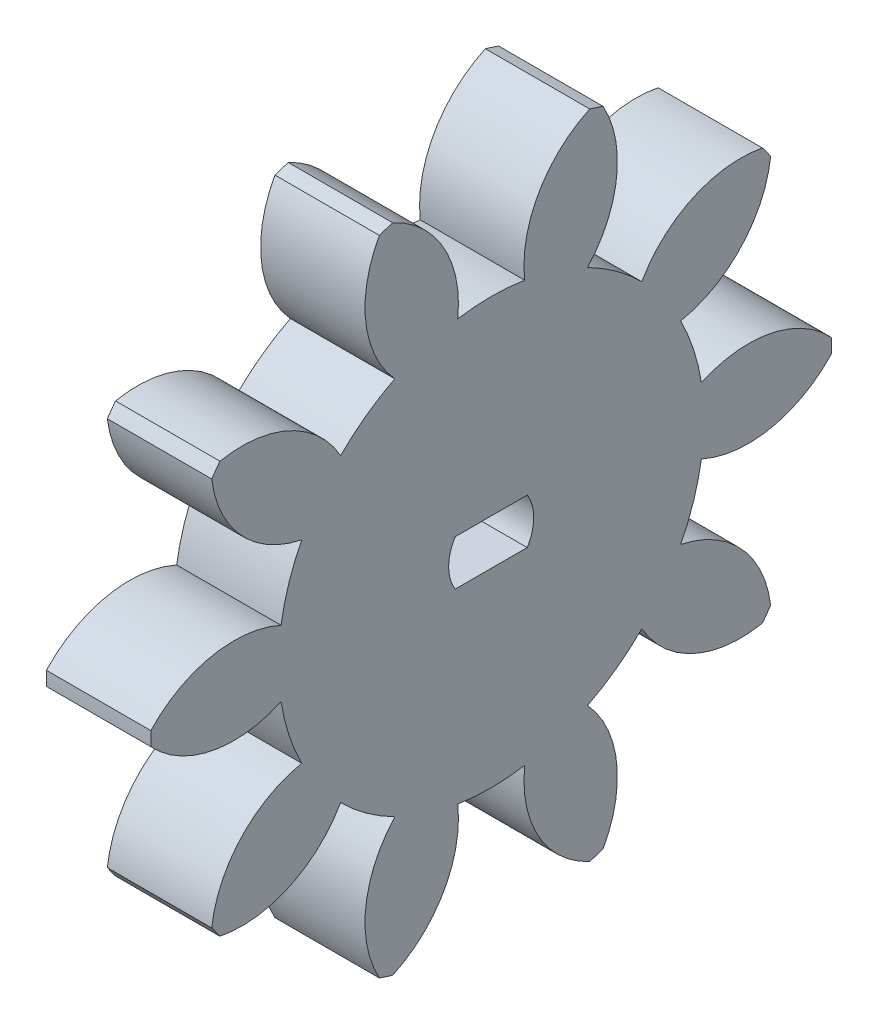
SolidWorks part; units mm, degrees
ref_plane "Plane1" through (0, 0, 0) normal (0, 0, 1) x (1, 0, 0)
ref_plane "Plane2" through (0, 0, 0) normal (0, 1, 0) x (1, 0, 0)
ref_plane "Plane3" through (0, 0, 0) normal (1, 0, 0) x (0, 0, -1)
sketch "HoldingSke" plane through (0, 0, 0) normal (0, 1, 0) x (1, 0, 0)
  line L0 (0, 0) -> (200.1129, -35.2853)
  line L1 (-15, 0) -> (100, 0) construction
  line L2 (0, 0) -> (-2.1039, 2.3779)
  line L3 (0, 0) -> (-11.863, 4.5341)
  line L4 (0, 0) -> (8.5048, 1.4996)
  line L5 (0, 0) -> (-47.5972, -17.7524)
  line L6 (0, 0) -> (-4.8428, -3.2675)
  line L7 (-2.1039, 2.3779) -> (8.8308, 51.9871)
  line L8 (-76.2, 54.61) -> (-71.1708, 54.61)
  line L9 (-71.009, 38.7566) -> (-53.1078, 45.2721)
  line L10 (-76.2, 71.12) -> (104.1128, 71.12)
  line L11 (0, 0) -> (-5.842, 0)
  line L12 (-76.2, 101.6) -> (-76.0857, 101.6)
  line L13 (24.9733, 27.94) -> (52.9518, 28.4284)
  line L14 (24.9733, 27.94) -> (24.9746, 27.94)
  line L15 (24.9733, 27.94) -> (100.4006, 29.5858)
  circle A0 centre (0, 0) radius 2.3812
  circle A1 centre (0, 0) radius 11.905
  circle A2 centre (0, 0) radius 38.1
  circle A3 centre (0, 0) radius 2.3812
  dimension "MHD" = 23.81
  dimension "Hub_dia" = 76.2
  dimension "Bore" = 4.7625
  dimension "MBD" = 4.7625
  dimension "Num_teeth" = 10
  dimension "Pitch" = 203.2
  dimension "Overall_len" = 50.8
  dimension "Show_teeth" = 10
  dimension "Thickness" = 5.842
  dimension "OAL" = 50.8001
  dimension "T_dim" = 5.0292
  dimension "Ap" = 20
  dimension "H" = 19.05
  dimension "Pitch_radius" = 180.3128
  dimension "Width" = 5.842
  dimension "Backlash" = 0.1143
  dimension "Addendum_fac" = 1
  dimension "Dedendum_fac" = 1.25
  dimension "Clearance_fac" = 0.25
  dimension "Dedendum_add" = 0.0013
sketch "BasProSke" plane through (0, 0, 0) normal (0, 1, 0) x (1, 0, 0)
  line L0 (-10, 0) -> (60, 0) construction
  line L1 (0, 0) -> (0, 19.05)
  line L2 (0, 0) -> (5.842, 0)
  line L3 (5.842, 0) -> (5.842, 19.05)
  line L4 (5.842, 19.05) -> (0, 19.05)
  dimension "Thickness" = 5.842
  dimension "Diameter" = 38.1
revolve "Base-Revolve" add sketch "BasProSke" angle 360 about L0
sketch "TooCutSke" plane through (0, 0, 0) normal (1, 0, 0) x (0, 0, -1)
  line L1 (0, 0) -> (0, 107) construction
  line L2 (0, 0) -> (-2.683, 15.6466) construction
  line L3 (0, 0) -> (-9.7093, 29.8821) construction
  line L4 (-2.683, 15.6466) -> (-4.8546, 14.941) construction
  arc A0 (1.8735, 11.7566) -> (-1.8735, 11.7566) centre (0, 0) ccw
  arc A1 (5.5485, 18.2506) -> (-5.5485, 18.2506) centre (0, 0) ccw
  circle A2 centre (0, 0) radius 15.875 construction
  circle A3 centre (0, 0) radius 14.9176 construction
  arc A4 (-1.8735, 11.7566) -> (-5.5485, 18.2506) centre (-8.183, 12.4729) ccw
  arc A5 (5.5485, 18.2506) -> (1.8735, 11.7566) centre (8.183, 12.4729) ccw
  dimension "Root_dia" = 23.81
  dimension "Overcut_dia" = 38.1508
  dimension "Pitch_dia" = 31.75
  dimension "Base_dia" = 29.8352
  dimension "Flank_rad" = 6.35
  dimension "Half_ang" = 18
  dimension "Half_CT" = 2.2834
extrude "ToothCut" cut sketch "TooCutSke" along normal through all
fillet "Breaks" [suppressed] radius 0.0635
fillet "RootFillets" [suppressed] radius 0.795
pattern_circular "TeethCuts" count 10 every 36 about axis through (-10, 0, 0) along (1, 0, 0) of "ToothCut", "RootFillets", "Breaks"
sketch "HubNeaOneSke" plane through (0, 0, 0) normal (-1, 0, 0) x (0, 0, 1)
  circle A0 centre (0, 0) radius 11.905
  dimension "Diameter" = 23.81
extrude "HubNearOne" [suppressed] add sketch "HubNeaOneSke" along normal blind 44.9581
sketch "HubNeaBotSke" plane through (0, 0, 0) normal (-1, 0, 0) x (0, 0, 1)
  circle A0 centre (0, 0) radius 11.905
  dimension "Diameter" = 23.81
extrude "HubNearBoth" [suppressed] add sketch "HubNeaBotSke" along normal blind 22.479
ref_plane "FarPln" through (5.842, 0, 0) normal (1, 0, 0) x (0, 0, -1)
sketch "HubFarSke" plane through (5.842, 0, 0) normal (1, 0, 0) x (0, 0, -1)
  circle A0 centre (0, 0) radius 11.905
  dimension "Diameter" = 23.81
extrude "HubFar" [suppressed] add sketch "HubFarSke" along normal blind 22.479
sketch "BorSke" plane through (0, 0, 0) normal (1, 0, 0) x (0, 0, -1)
  circle A0 centre (0, 0) radius 2.3812
  dimension "Diameter" = 4.7625
extrude "Bore" cut sketch "BorSke" along normal mid plane 101.6001
sketch "KeySke" plane through (0, 0, 0) normal (1, 0, 0) x (0, 0, -1)
  line L0 (-0.127, 0) -> (-0.127, 2.6479)
  line L1 (-0.127, 2.6479) -> (0.127, 2.6479)
  line L2 (0.127, 2.6479) -> (0.127, 0)
  line L3 (0, 0) -> (0, 34) construction
  line L4 (-0.127, 0) -> (0.127, 0)
  dimension "Offset" = 2.648
  dimension "Width" = 0.254
extrude "Keyway" [suppressed] cut sketch "KeySke" along normal mid plane 101.6001
pattern_circular "Keyway2" [suppressed] count 2 every 90 about axis through (-10, 0, 0) along (1, 0, 0)
sketch "Sketch1" plane through (5.842, 0, 0) normal (1, 0, 0) x (0, 0, -1)
  line L0 (-4.4067, 4.572) -> (4.4067, 4.572)
  arc A0 (4.4067, 4.572) -> (-4.4067, 4.572) centre (0, 0) ccw
  point P5 (0, -6.35)
  dimension "D1" = 10.922
extrude "Boss-Extrude1" add sketch "Sketch1" against normal up to surface (5.842 mm away) up to face at (0, 0, -2.3812)
sketch "Sketch2" plane through (5.842, 0, 0) normal (1, 0, 0) x (0, 0, -1)
  line L0 (-2.177, 1.27) -> (2.177, 1.27)
  line L1 (-2.177, -1.27) -> (2.177, -1.27)
  line L2 (0, 1.27) -> (0, -1.27) construction
  arc A0 (-2.177, -1.27) -> (2.177, -1.27) centre (0, 0) ccw
  arc A1 (2.177, 1.27) -> (-2.177, 1.27) centre (0, 0) ccw
  point P9 (0, 0)
  point P10 (0, 0)
  dimension "D1" = 2.54
extrude "Boss-Extrude2" add sketch "Sketch2" against normal up to surface (5.842 mm away) up to face at (0, 0, -2.3812)
equation "' \"Pitch@HoldingSke\" = 4"
equation "' \"Num_teeth@HoldingSke\" = 12"
equation "' \"Ap@HoldingSke\" =  20"
equation "' \"Ap@HoldingSke\" = 20"
equation "' \"Width@HoldingSke\" = 0.5"
equation "' \"Hub_dia@HoldingSke\"= 1"
equation "' \"Hub_dia@HoldingSke\" = 1"
equation "' \"Overall_len@HoldingSke\" = 1.0"
equation "' \"Bore@HoldingSke\" = 0.75"
equation "' \"T_dim@HoldingSke\" = 0.85"
equation "' \"Width@KeySke\" = 0.25"
equation "' \"Show_teeth@HoldingSke\" = 13"
equation "' \"Backlash@HoldingSke\" = 0.009"
equation "' \"Addendum_fac@HoldingSke\" = 1.0"
equation "' \"Dedendum_fac@HoldingSke\" = 1.25"
equation "' \"Dedendum_add@HoldingSke\" = 0.00005"
equation "' \"Clearance_fac@HoldingSke\" = 0.25"
equation "' \"Pitch@HoldingSke\" = 0.5"
equation "' \"Num_teeth@HoldingSke\" = 23"
equation "' \"Show_teeth@HoldingSke\" = 23"
equation "' \"Backlash@HoldingSke\" = 0.0375"
equation "\"Overcut_dia@TooCutSke\" = (\"Num_teeth@HoldingSke\" + 2 * \"Addendum_fac@HoldingSke\") / \"Pitch@HoldingSke\" + 0.002"
equation "\"Pitch_dia@TooCutSke\" = \"Num_teeth@HoldingSke\" / \"Pitch@HoldingSke\""
equation "\"Base_dia@TooCutSke\" = \"Num_teeth@HoldingSke\" / \"Pitch@HoldingSke\" * cos((\"Ap@HoldingSke\"  * 3.14159265 / 180))"
equation "\"Root_dia@TooCutSke\" = (\"Num_teeth@HoldingSke\" + 2) / \"Pitch@HoldingSke\" - 2 * (\"Addendum_fac@HoldingSke\" + \"Dedendum_fac@HoldingSke\") / \"Pitch@HoldingSke\" - \"Dedendum_add@HoldingSke\" * 2"
equation "\"Half_ang@TooCutSke\" = 180 / \"Num_teeth@HoldingSke\""
equation "\"Half_CT@TooCutSke\" = \"Num_teeth@HoldingSke\" / \"Pitch@HoldingSke\" * sin((3.14159265 / 2 / \"Num_teeth@HoldingSke\")) / 2 - 7 * \"Backlash@HoldingSke\" / 4"
equation "\"Flank_rad@TooCutSke\" = \"Num_teeth@HoldingSke\" / \"Pitch@HoldingSke\" / 5"
equation "\"Radius@RootFillets\" = \"Clearance_fac@HoldingSke\" / \"Pitch@HoldingSke\" + \"Dedendum_add@HoldingSke\""
equation "\"Break_rad@Breaks\" = 0.02 / \"Pitch@HoldingSke\""
equation "\"Thickness@HoldingSke\" = \"Width@HoldingSke\""
equation "\"OAL@HoldingSke\" = \"Thickness@HoldingSke\""
equation "\"MHD@HoldingSke\" = (\"Num_teeth@HoldingSke\" + 2) / \"Pitch@HoldingSke\" - 2 * (\"Addendum_fac@HoldingSke\" + \"Dedendum_fac@HoldingSke\")  / \"Pitch@HoldingSke\" - \"Dedendum_add@HoldingSke\" * 2"
equation "\"MBD@HoldingSke\" = (\"Num_teeth@HoldingSke\" + 2) / \"Pitch@HoldingSke\" - 2 * (\"Addendum_fac@HoldingSke\" + \"Dedendum_fac@HoldingSke\")  / \"Pitch@HoldingSke\" - \"Dedendum_add@HoldingSke\" * 2 - 0.002"
equation "\"MHD@HoldingSke\" = ((sgn( \"MHD@HoldingSke\" - \"Hub_dia@HoldingSke\" )-1)*( \"MHD@HoldingSke\" - \"Hub_dia@HoldingSke\" ))/-2+ \"Hub_dia@HoldingSke\""
equation "\"MBD@HoldingSke\" = ((sgn( \"MBD@HoldingSke\" - \"Bore@HoldingSke\" )-1)*( \"MBD@HoldingSke\" - \"Bore@HoldingSke\" ))/-2+ \"Bore@HoldingSke\""
equation "\"OAL@HoldingSke\" = ((sgn( \"OAL@HoldingSke\" - \"Overall_len@HoldingSke\" )+1)*( \"OAL@HoldingSke\" - \"Overall_len@HoldingSke\" ))/2 + \"Overall_len@HoldingSke\" + 0.000002"
equation "\"Num_teeth@TeethCuts\" = int( \"Show_teeth@HoldingSke\" ) + 1"
equation "\"Num_teeth@TeethCuts\" = ((sgn( \"Num_teeth@TeethCuts\" - \"Num_teeth@HoldingSke\" )-1)*( \"Num_teeth@TeethCuts\" - \"Num_teeth@HoldingSke\" ))/-2+ \"Num_teeth@HoldingSke\""
equation "\"Num_teeth@TeethCuts\" = ((sgn( \"Num_teeth@TeethCuts\" - 2.0)+1)*( \"Num_teeth@TeethCuts\" - 2.0))/2 +2.0"
equation "\"Angle@TeethCuts\" = 360.0 / \"Num_teeth@HoldingSke\""
equation "\"Diameter@BasProSke\" = (\"Num_teeth@HoldingSke\" + 2 * \"Addendum_fac@HoldingSke\") / \"Pitch@HoldingSke\""
equation "\"Thickness@BasProSke\"  = \"Thickness@HoldingSke\""
equation "' \"Fillet_rad@BasProSke\" =  \"Thickness@HoldingSke\" * 0.05"
equation "' \"Fillet_rad@BasProSke\" = \"Thickness@HoldingSke\" * 0.05"
equation "\"MHD@HoldingSke\" = ((sgn( \"MHD@HoldingSke\" - \"Root_dia@TooCutSke\" )-1)*( \"MHD@HoldingSke\" - \"Root_dia@TooCutSke\" ))/-2+ \"Root_dia@TooCutSke\""
equation "\"Diameter@HubNeaOneSke\" = \"MHD@HoldingSke\""
equation "\"Length@HubNearOne\" = \"OAL@HoldingSke\" - \"Thickness@BasProSke\""
equation "\"Diameter@HubNeaBotSke\" = \"MHD@HoldingSke\""
equation "\"Length@HubNearBoth\" = ( \"OAL@HoldingSke\" - \"Thickness@BasProSke\" ) / 2.0"
equation "\"Thickness@FarPln\" = \"Thickness@BasProSke\""
equation "\"Diameter@HubFarSke\" = \"MHD@HoldingSke\""
equation "\"Length@HubFar\" = ( \"OAL@HoldingSke\" - \"Thickness@BasProSke\" ) / 2.0"
equation "\"Diameter@BorSke\" = \"MBD@HoldingSke\""
equation "\"D1@Bore\" = \"OAL@HoldingSke\" * 2.0"
equation "\"D1@Keyway\" = \"OAL@HoldingSke\" * 2.0"
equation "\"Offset@KeySke\" = \"T_dim@HoldingSke\" - \"MBD@HoldingSke\" / 2.0"
